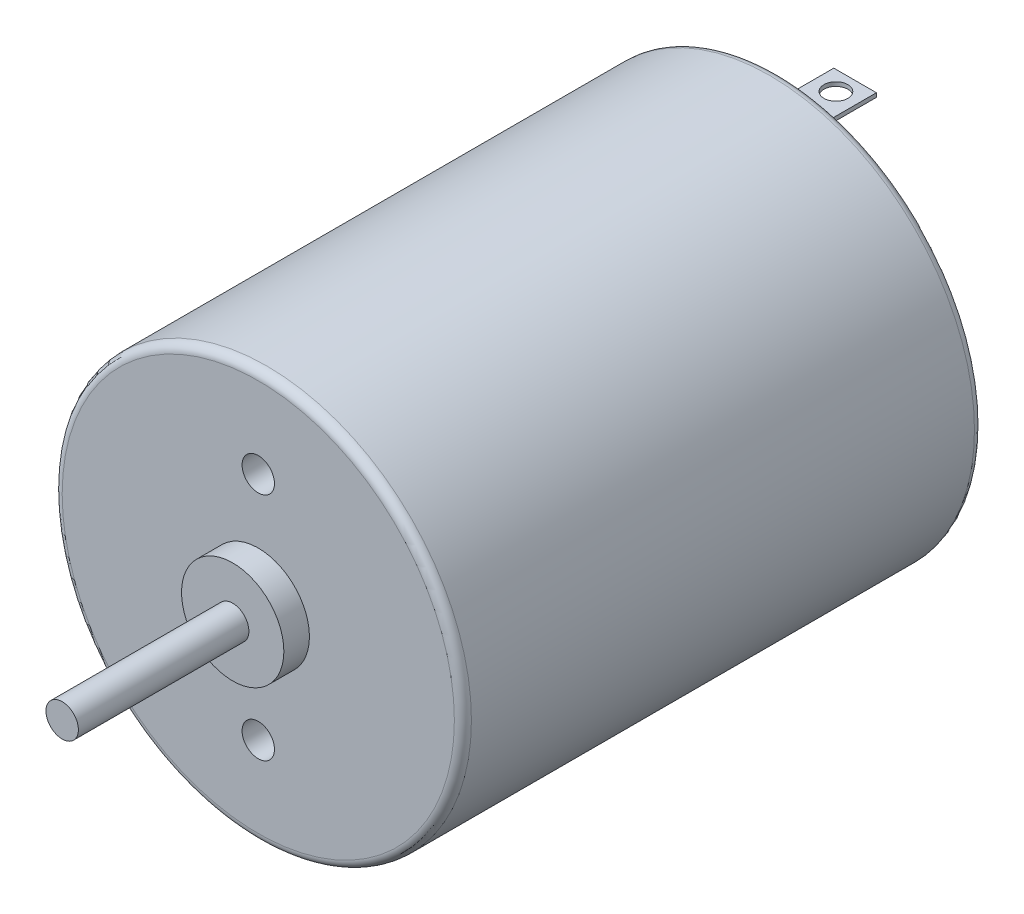
SolidWorks part; units mm, degrees
ref_plane "Plan de face" through (0, 0, 0) normal (0, 0, 1) x (1, 0, 0)
ref_plane "Plan de dessus" through (0, 0, 0) normal (0, 1, 0) x (1, 0, 0)
ref_plane "Plan de droite" through (0, 0, 0) normal (1, 0, 0) x (0, 0, -1)
sketch "Esquisse1" plane through (0, 0, 0) normal (0, 0, 1) x (1, 0, 0)
  circle A0 centre (0, 0) radius 12
extrude "Boss.-Extru.1" add sketch "Esquisse1" along normal blind 30.5
sketch "Esquisse2" plane through (0, 0, 0) normal (0, 0, -1) x (-1, 0, 0)
  circle A0 centre (0, 0) radius 4.5
extrude "Boss.-Extru.2" add sketch "Esquisse2" along normal blind 2
sketch "Esquisse3" plane through (0, 0, 30.5) normal (0, 0, 1) x (1, 0, 0)
  circle A0 centre (0, 0) radius 3
extrude "Boss.-Extru.3" add sketch "Esquisse3" along normal blind 1.5
sketch "Esquisse4" plane through (0, 0, 0) normal (0, 0, -1) x (-1, 0, 0)
  line L0 (0, 0) -> (0, 12)
  line L1 (0, 12) -> (0, -12)
  line L2 (-1.25, 9.0128) -> (1.25, 9.0128)
  line L3 (0, 9.25) -> (1.25, 9.25)
  line L4 (0, 9.25) -> (0, 8.7488)
  line L6 (1.25, 9.25) -> (1.25, 9.0128)
  line L7 (0, 9.25) -> (-1.25, 9.25)
  line L8 (0, 9.25) -> (0, 8.7488)
  line L10 (-1.25, 9.25) -> (-1.25, 9.0128)
  line L11 (0, 0) -> (-12, 0)
  line L12 (-12, 0) -> (12, 0)
  line L13 (0, -9.25) -> (1.25, -9.25)
  line L14 (1.25, -9.25) -> (1.25, -9.0128)
  line L15 (-1.25, -9.25) -> (-1.25, -9.0128)
  line L16 (-1.25, -9.0128) -> (1.25, -9.0128)
  line L17 (0, -9.25) -> (-1.25, -9.25)
  circle A0 centre (0, 0) radius 9.25
  circle A1 centre (0, 0) radius 12 construction
  point P14 (1.25, 9.1314)
  dimension "D1" = 1.25
  dimension "D2" = 1.25
extrude "Boss.-Extru.4" add sketch "Esquisse4" along normal blind 4.5 contours L15 A0 L1 L16 | A0 L15 L17 | L1 A0 L14 L16 | A0 L13 L14 | L6 A0 L1 L2 | A0 L6 L3 | L1 A0 L10 L2 | A0 L7 L10
sketch "Esquisse5" plane through (0, 9.25, 0) normal (0, 1, 0) x (1, 0, 0)
  line L0 (0, 4.5) -> (0, 0)
  line L1 (1.25, 4.5) -> (-1.25, 4.5) construction
  line L2 (1.25, 0) -> (-1.25, 0) construction
  line L3 (0, 2.25) -> (0, 4.5)
  circle A0 centre (0, 3.375) radius 0.7
extrude "Enlèv. mat.-Extru.1" cut sketch "Esquisse5" against normal blind 29.5 contours L3 A0 | L3 A0
sketch "Esquisse6" plane through (0, 0, 32) normal (0, 0, 1) x (1, 0, 0)
  circle A0 centre (0, 0) radius 0.95
extrude "Boss.-Extru.5" add sketch "Esquisse6" along normal blind 10
sketch "Esquisse7" plane through (0, 0, -2) normal (0, 0, -1) x (-1, 0, 0)
  circle A0 centre (0, 0) radius 0.95
extrude "Enlèv. mat.-Extru.2" cut sketch "Esquisse7" against normal blind 0.2
fillet "Congé1" radius 0.5 1 edges at (12, 0, 30.5)
fillet "Congé2" radius 0.5 10 edges at (12, 0, 0) (-4.5, 0, 0) (-1.25, -9.1314, 0) (0, -9.0128, 0) (1.25, -9.1314, 0) (0, -9.25, 0) (1.25, 9.1314, 0) (0, 9.0128, 0) (-1.25, 9.1314, 0) (0, 9.25, 0)
sketch "Esquisse8" plane through (0, 0, 30.5) normal (0, 0, 1) x (1, 0, 0)
  line L0 (0, 0) -> (0, 11.5)
  line L1 (0, 11.5) -> (0, -11.5)
  circle A0 centre (0, 0) radius 6.75
  circle A1 centre (0, 0) radius 11.5 construction
  circle A2 centre (0, 6.75) radius 0.95
  circle A3 centre (0, -6.75) radius 0.95
extrude "Enlèv. mat.-Extru.3" cut sketch "Esquisse8" against normal blind 20 contours L1 A2 A0 | A0 A2 L1 | A0 A2 L1 | L1 A2 A0 | L1 A3 A0 | A0 A3 L1 | L1 A3 A0 | A0 A3 L1
